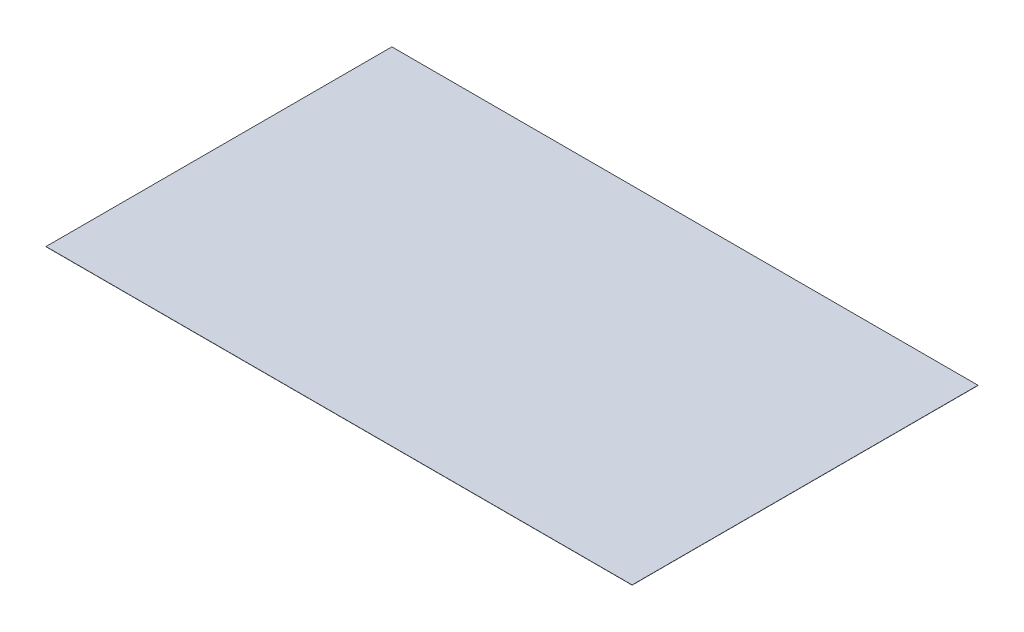
SolidWorks part; units mm, degrees
ref_plane "前视基准面" through (0, 0, 0) normal (0, 0, 1) x (1, 0, 0)
ref_plane "上视基准面" through (0, 0, 0) normal (0, 1, 0) x (1, 0, 0)
ref_plane "右视基准面" through (0, 0, 0) normal (1, 0, 0) x (0, 0, -1)
other "Configuration Table"
sketch "草图1" plane through (0, 0, 0) normal (0, 1, 0) x (1, 0, 0)
  line L1 (-170.5916, 95.9187) -> (160.177, 95.9187)
  line L2 (-170.5916, 95.9187) -> (-170.5916, -99.2514)
  line L3 (-170.5916, -99.2514) -> (160.177, -99.2514)
  line L4 (160.177, 95.9187) -> (160.177, -99.2514)
extrude "凸台-拉伸1" add sketch "草图1" along normal blind 0.1
